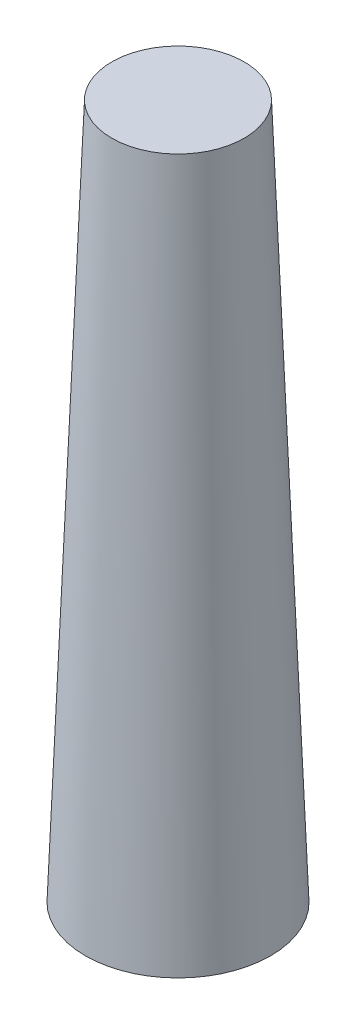
SolidWorks part; units mm, degrees
material "ABS"
ref_plane "Front Plane" through (0, 0, 0) normal (0, 0, 1) x (1, 0, 0)
ref_plane "Top Plane" through (0, 0, 0) normal (0, 1, 0) x (1, 0, 0)
ref_plane "Right Plane" through (0, 0, 0) normal (1, 0, 0) x (0, 0, -1)
sketch "Sketch1" plane through (0, 0, 0) normal (0, 1, 0) x (1, 0, 0)
  circle A0 centre (0, 0) radius 5.08
  dimension "D1" = 10.16
ref_plane "Plane1" through (0, 38.1, 0) normal (0, 1, 0) x (1, 0, 0)
sketch "Sketch2" plane through (0, 38.1, 0) normal (0, 1, 0) x (1, 0, 0)
  circle A0 centre (0, 0) radius 3.6286
  dimension "D1" = 7.2571
loft "Loft1" add profiles "Sketch2", "Sketch1"
